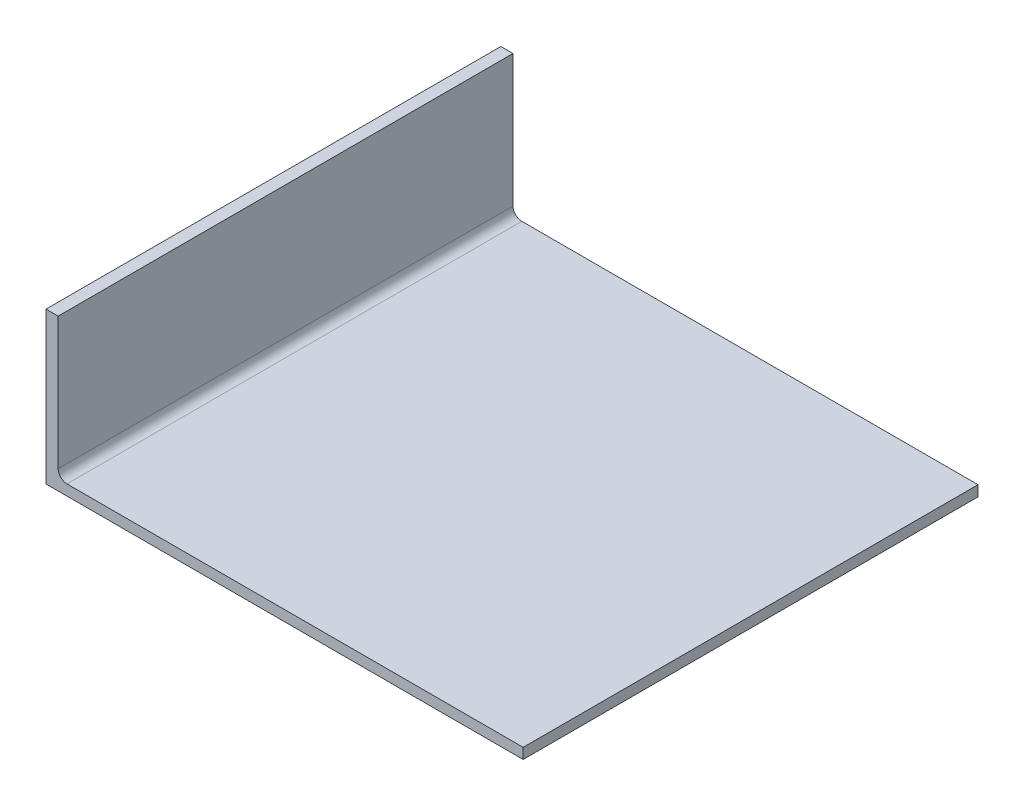
SolidWorks part; units mm, degrees
ref_plane "Front Plane" through (0, 0, 0) normal (0, 0, 1) x (1, 0, 0)
ref_plane "Top Plane" through (0, 0, 0) normal (0, 1, 0) x (1, 0, 0)
ref_plane "Right Plane" through (0, 0, 0) normal (1, 0, 0) x (0, 0, -1)
sketch "Sketch1" plane through (0, 0, 0) normal (0, 1, 0) x (1, 0, 0)
  line L1 (8.7553, 21.2243) -> (-262.1325, 21.2243)
  line L2 (8.7553, 21.2243) -> (8.7553, -236.9969)
  line L3 (8.7553, -236.9969) -> (-262.1325, -236.9969)
  line L6 (-262.1325, 21.2243) -> (-262.1325, -236.9969)
extrude "Base" add sketch "Sketch1" along normal blind 6
sketch "Sketch2" plane through (0, 6, 0) normal (0, 1, 0) x (1, 0, 0)
  line L0 (-262.1325, -236.9969) -> (8.7553, -236.9969) construction
  line L1 (-262.1325, 21.2243) -> (-255.2403, 21.2243)
  line L2 (-262.1325, 21.2243) -> (-262.1325, -236.9969)
  line L3 (-262.1325, -236.9969) -> (-255.2403, -236.9969)
  line L4 (-255.2403, 21.2243) -> (-255.2403, -236.9969)
extrude "Boss-Extrude2" add sketch "Sketch2" along normal blind 80
fillet "Fillet1" radius 5 1 edges at (-255.2403, 6, 107.8863)
